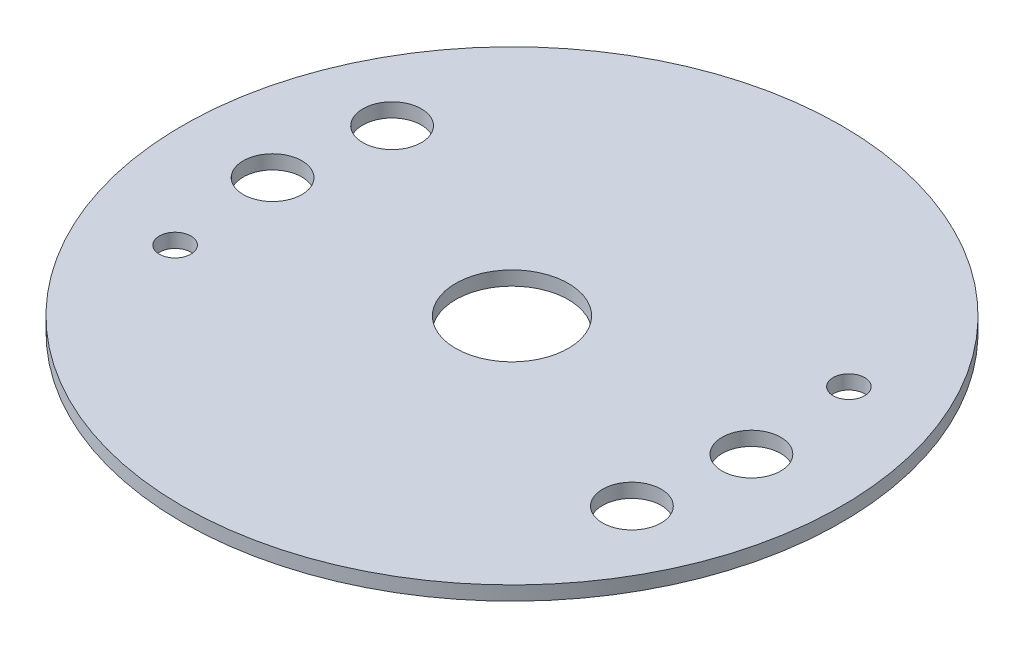
SolidWorks part; units mm, degrees
ref_plane "Front Plane" through (0, 0, 0) normal (0, 0, 1) x (1, 0, 0)
ref_plane "Top Plane" through (0, 0, 0) normal (0, 1, 0) x (1, 0, 0)
ref_plane "Right Plane" through (0, 0, 0) normal (1, 0, 0) x (0, 0, -1)
sketch "Sketch1" plane through (0, 0, 0) normal (0, 1, 0) x (1, 0, 0)
  circle A0 centre (0, 0) radius 74.295
  circle A1 centre (0, 0) radius 12.7
extrude "Boss-Extrude1" add sketch "Sketch1" along normal blind 3.175
sketch "Sketch2" plane through (0, 3.175, 0) normal (0, 1, 0) x (1, 0, 0)
  line L0 (53.975, 0) -> (-53.975, 0) construction
  line L1 (51.7955, 24.1526) -> (-51.7955, -24.1526) construction
  line L2 (0, 0) -> (50.6445, -23.6159) construction
  line L3 (0, 0) -> (-50.6445, 23.6159) construction
  circle A0 centre (-53.975, 0) radius 6.604
  circle A1 centre (53.975, 0) radius 6.604
  circle A2 centre (-51.7955, -24.1526) radius 3.556
  circle A3 centre (51.7955, 24.1526) radius 3.556
  circle A4 centre (50.6445, -23.6159) radius 6.604
  circle A5 centre (-50.6445, 23.6159) radius 6.604
  point P4 (0, 0)
  point P8 (0, 0)
extrude "Cut-Extrude1" cut sketch "Sketch2" against normal blind 3.175
